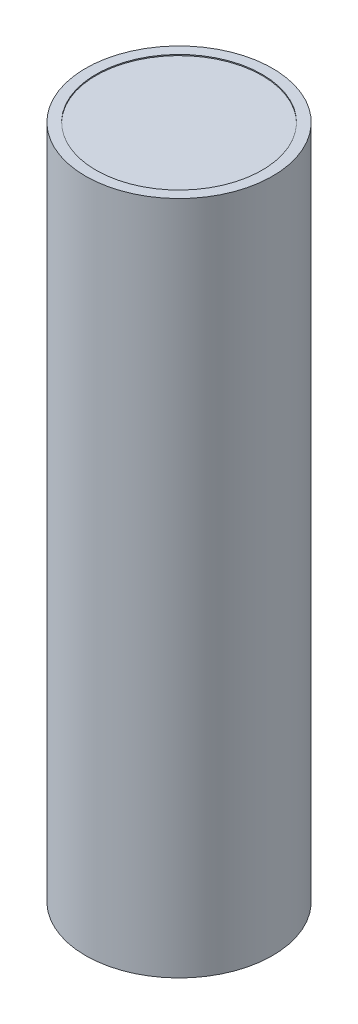
SolidWorks part; units mm, degrees
material "ABS"
ref_plane "Front Plane" through (0, 0, 0) normal (0, 0, 1) x (1, 0, 0)
ref_plane "Top Plane" through (0, 0, 0) normal (0, 1, 0) x (1, 0, 0)
ref_plane "Right Plane" through (0, 0, 0) normal (1, 0, 0) x (0, 0, -1)
sketch "Sketch1" plane through (0, 0, 0) normal (0, 1, 0) x (1, 0, 0)
  circle A0 centre (0, 0) radius 9
  dimension "D1" = 18
extrude "Boss-Extrude1" add sketch "Sketch1" along normal blind 65
sketch "Sketch2" plane through (0, 65, 0) normal (0, 1, 0) x (1, 0, 0)
  circle A0 centre (0, 0) radius 8
  circle A1 centre (0, 0) radius 9 construction
  dimension "D1" = 1
extrude "Cut-Extrude1" cut sketch "Sketch2" against normal blind 0.1
ref_plane "Plane1" through (0, 32.5, 0) normal (0, 1, 0) x (1, 0, 0)
mirror "Mirror1" about plane through (0, 32.5, 0) normal (0, 1, 0) of "Cut-Extrude1"
